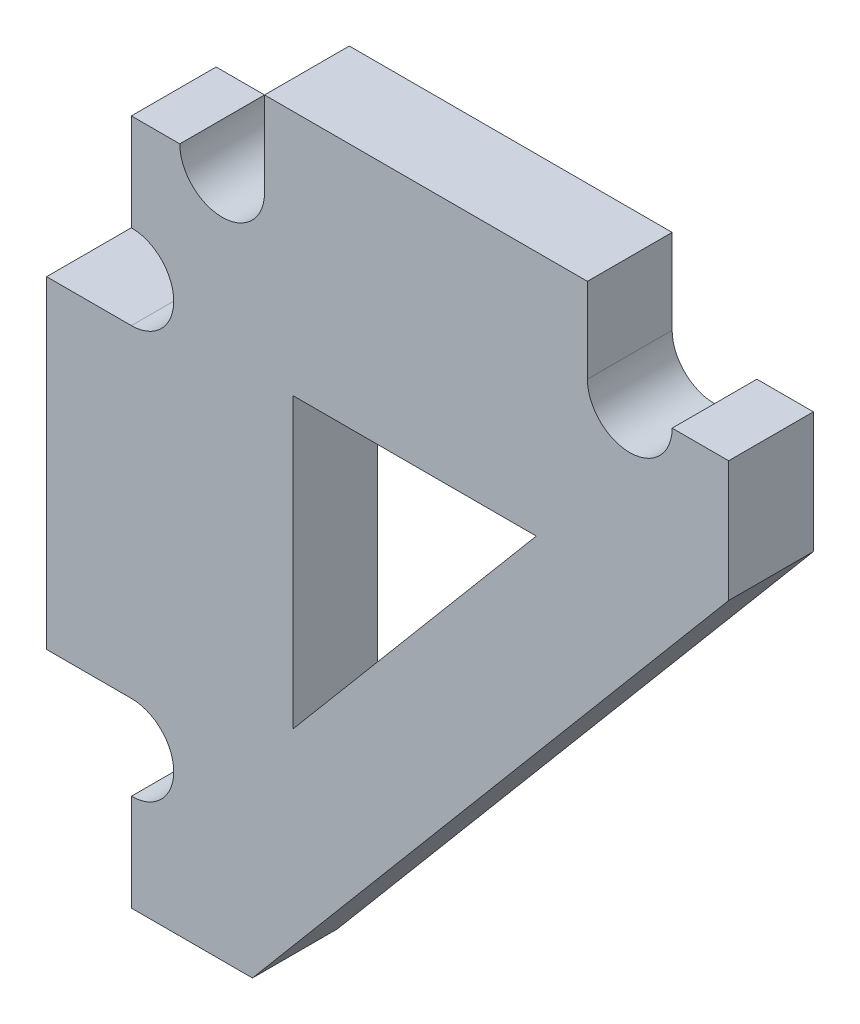
SolidWorks part; units mm, degrees
material "Thornel Mat VMA"
ref_plane "前视基准面" through (0, 0, 0) normal (0, 0, 1) x (1, 0, 0)
ref_plane "上视基准面" through (0, 0, 0) normal (0, 1, 0) x (1, 0, 0)
ref_plane "右视基准面" through (0, 0, 0) normal (1, 0, 0) x (0, 0, -1)
sketch "草图1" plane through (0, 0, 0) normal (0, 0, 1) x (1, 0, 0)
  line L0 (0, 0) -> (0, -4.5)
  line L1 (0, -4.5) -> (-2.1, -4.5)
  line L2 (-2.1, -4.5) -> (-2.1, -12.5)
  line L3 (-2.1, -12.5) -> (0, -12.5)
  line L4 (0, -12.5) -> (0, -17)
  line L5 (0, -17) -> (3, -17)
  line L6 (3, -17) -> (14.8, -3)
  line L7 (14.8, -3) -> (14.8, 0)
  line L8 (14.8, 0) -> (11.3, 0)
  line L9 (11.3, 0) -> (11.3, 2.1)
  line L10 (11.3, 2.1) -> (3.3, 2.1)
  line L11 (3.3, 2.1) -> (3.3, 0)
  line L12 (3.3, 0) -> (0, 0)
  line L13 (-2.1, -8.5) -> (1.5897, -8.5) construction
  line L14 (7.3, 2.1) -> (7.3, -1.0483) construction
  line L15 (4, -4) -> (4, -11.1586)
  line L16 (4, -11.1586) -> (10.0337, -4)
  line L17 (10.0337, -4) -> (4, -4)
  circle A0 centre (2.25, 0) radius 1.05
  circle A1 centre (12.35, 0) radius 1.05
  circle A3 centre (0, -13.55) radius 1.05
  circle A4 centre (0, -3.45) radius 1.05
  dimension "D10" = 2.1
  dimension "D1" = 8
  dimension "D2" = 8.5
  dimension "D3" = 2.1
  dimension "D4" = 7.3
  dimension "D5" = 8
  dimension "D6" = 3
  dimension "D7" = 3
  dimension "D8" = 17
  dimension "D9" = 14.8
  dimension "D11" = 4
  dimension "D12" = 4
  dimension "D13" = 3
  dimension "D14" = 2.1
extrude "凸台-拉伸1" add sketch "草图1" along normal blind 2.1 contours A4 L1 L2 L3 A3 L4 L5 L6 L7 L8 A1 L9 L10 L11 A0 L12 L0 L17 L16 L15
